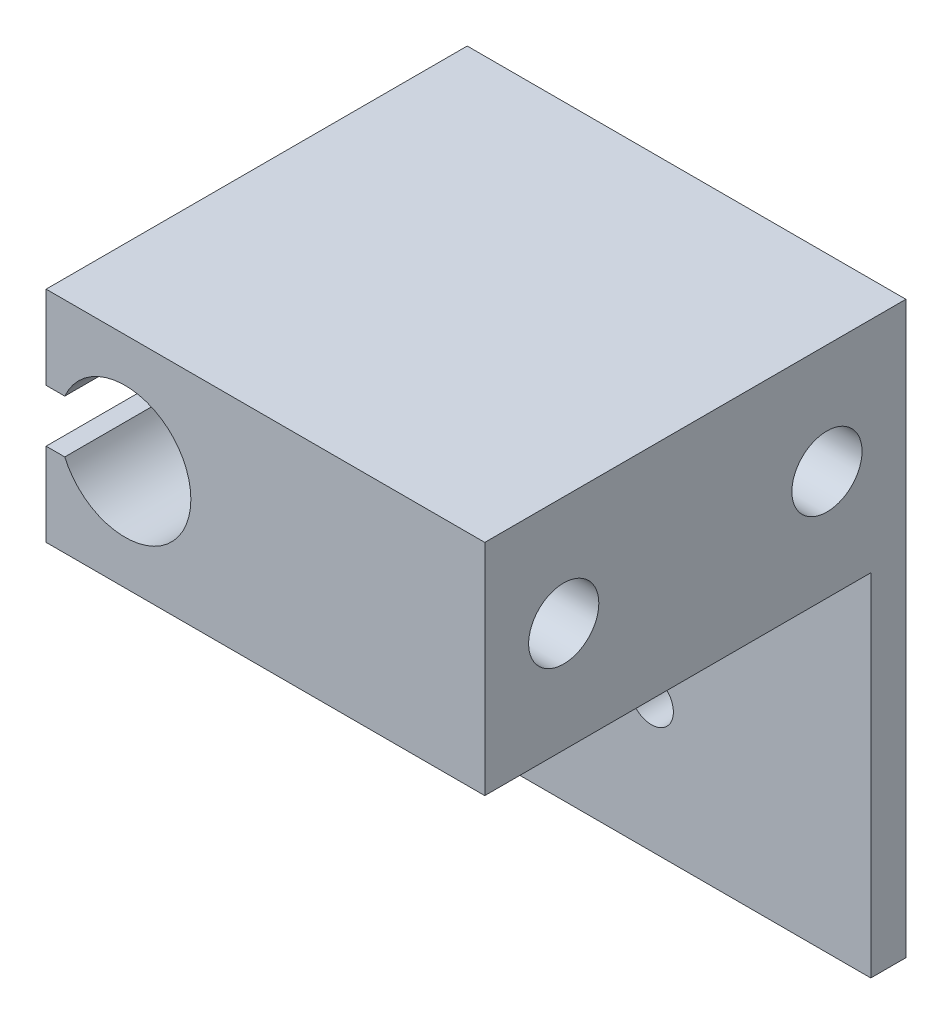
SolidWorks part; units mm, degrees
ref_plane "Front Plane" through (0, 0, 0) normal (0, 0, 1) x (1, 0, 0)
ref_plane "Top Plane" through (0, 0, 0) normal (0, 1, 0) x (1, 0, 0)
ref_plane "Right Plane" through (0, 0, 0) normal (1, 0, 0) x (0, 0, -1)
sketch "Sketch1" plane through (0, 0, 0) normal (0, 0, 1) x (1, 0, 0)
  line L0 (-22.8739, 3) -> (-25, 3)
  line L1 (-25, -12.5) -> (25, -12.5)
  line L2 (-25, -12.5) -> (-25, -3)
  line L3 (-25, 12.5) -> (25, 12.5)
  line L4 (25, -12.5) -> (25, 12.5)
  line L5 (-25, -12.5) -> (25, 12.5) construction
  line L6 (-25, 12.5) -> (25, -12.5) construction
  line L7 (-25, -3) -> (-22.8739, -3)
  line L8 (-25, 3) -> (-25, 12.5)
  arc A0 (-22.8739, -3) -> (-22.8739, 3) centre (-16, 0) ccw
  point P0 (0, 0)
  dimension "D1" = 15
  dimension "D2" = 16
  dimension "D3" = 6
  dimension "D4" = 50
  dimension "D5" = 25
extrude "Boss-Extrude1" add sketch "Sketch1" along normal mid plane 48
sketch "Sketch2" plane through (25, 0, 0) normal (1, 0, 0) x (0, 0, -1)
  circle A0 centre (-15, 0) radius 4
  circle A1 centre (15, 0) radius 4
  dimension "D1" = 8
  dimension "D2" = 15
  dimension "D3" = 15
extrude "Cut-Extrude1" cut sketch "Sketch2" against normal blind 30
sketch "Sketch3" plane through (0, -12.5, 0) normal (0, -1, 0) x (1, 0, 0)
  line L0 (-25, 24) -> (-25, -24) construction
  line L1 (25, 24) -> (-25, 24)
  line L2 (25, 24) -> (25, 20)
  line L3 (25, 20) -> (-25, 20)
  line L4 (-25, 24) -> (-25, 20)
  dimension "D1" = 4
extrude "Boss-Extrude2" [suppressed] add sketch "Sketch3" along normal blind 50
sketch "Sketch4" [suppressed] plane through (0, 0, 20) normal (0, 0, -1) x (-1, 0, 0)
  line L0 (15.5, -22) -> (-15.5, -53) construction
  line L1 (25, -62.5) -> (-25, -62.5) construction
  line L2 (25, -62.5) -> (25, -12.5) construction
  circle A0 centre (-15.5, -22) radius 1.75
  circle A1 centre (15.5, -22) radius 1.75
  circle A2 centre (15.5, -53) radius 1.75
  circle A3 centre (-15.5, -53) radius 1.75
  circle A4 centre (0, -37.5) radius 11.1
  point P8 (0, -37.5)
  dimension "D4" = 3.5
  dimension "D6" = 22.2
  dimension "D1" = 31
  dimension "D2" = 31
  dimension "D3" = 25
  dimension "D5" = 25
extrude "Cut-Extrude2" [suppressed] cut sketch "Sketch4" against normal through all
sketch "Sketch5" plane through (0, 0, -24) normal (0, 0, -1) x (-1, 0, 0)
  line L0 (25, -12.5) -> (-25, -12.5) construction
  line L1 (-25, -12.5) -> (25, -12.5)
  line L2 (-25, -12.5) -> (-25, -52.5)
  line L3 (-25, -52.5) -> (25, -52.5)
  line L4 (25, -12.5) -> (25, -52.5)
  circle A0 centre (0, -37.5) radius 2.5
  dimension "D3" = 5
  dimension "D1" = 40
  dimension "D2" = 25
extrude "Boss-Extrude3" add sketch "Sketch5" against normal blind 4
